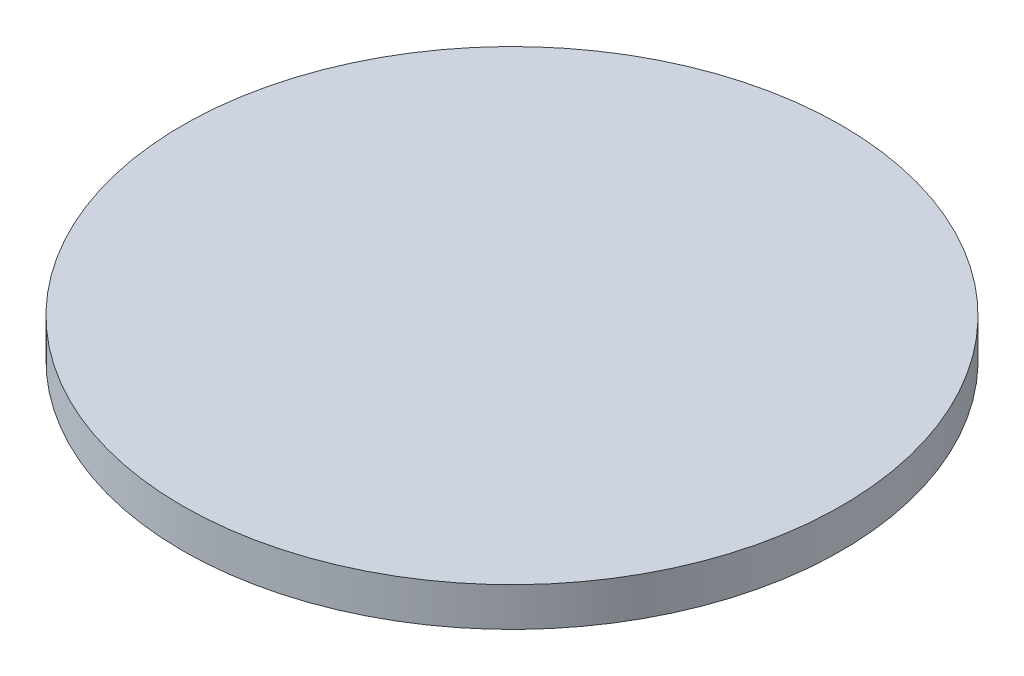
SolidWorks part; units mm, degrees
material "Oak"
ref_plane "Front Plane" through (0, 0, 0) normal (0, 0, 1) x (1, 0, 0)
ref_plane "Top Plane" through (0, 0, 0) normal (0, 1, 0) x (1, 0, 0)
ref_plane "Right Plane" through (0, 0, 0) normal (1, 0, 0) x (0, 0, -1)
sketch "Sketch1" plane through (0, 0, 0) normal (0, 1, 0) x (1, 0, 0)
  circle A0 centre (0, 0) radius 17
extrude "Boss-Extrude1" add sketch "Sketch1" along normal blind 2
